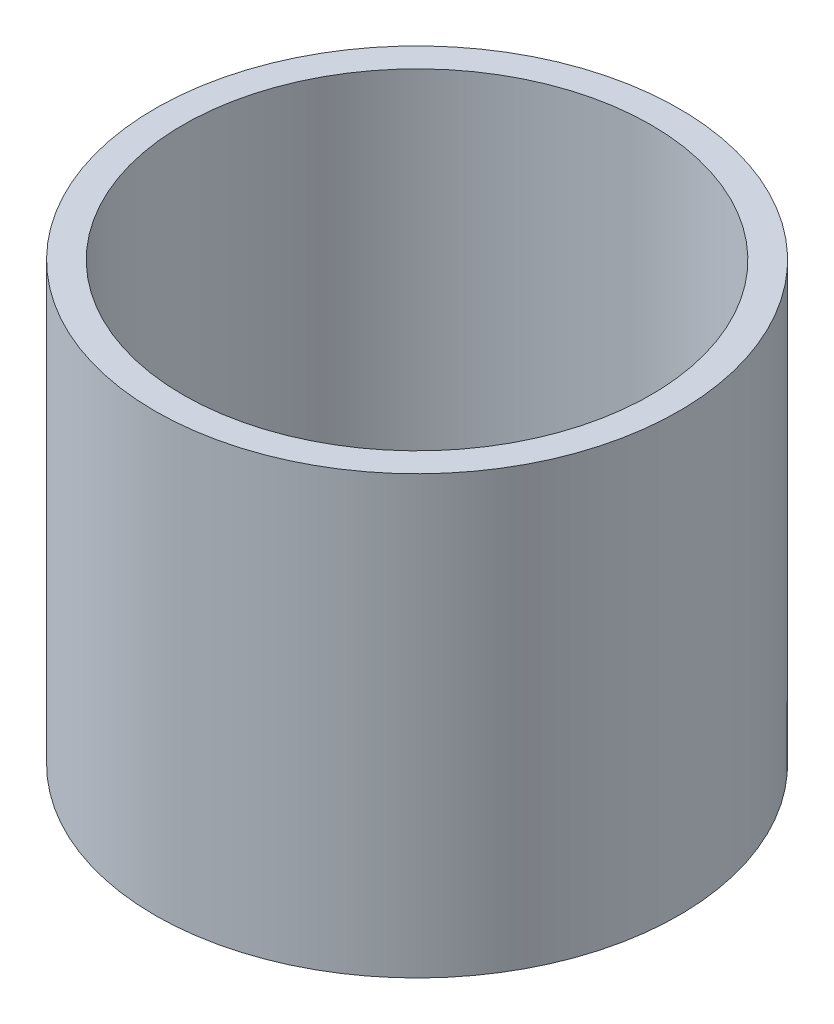
SolidWorks part; units mm, degrees
material "E-Glass Fiber"
ref_plane "Front Plane" through (0, 0, 0) normal (0, 0, 1) x (1, 0, 0)
ref_plane "Top Plane" through (0, 0, 0) normal (0, 1, 0) x (1, 0, 0)
ref_plane "Right Plane" through (0, 0, 0) normal (1, 0, 0) x (0, 0, -1)
sketch "Sketch1" plane through (0, 0, 0) normal (0, 1, 0) x (1, 0, 0)
  circle A1 centre (0, 0) radius 84
  circle A2 centre (0, 0) radius 75
  dimension "D1" = 150
  dimension "D2" = 9
extrude "Boss-Extrude1" add sketch "Sketch1" along normal blind 140
